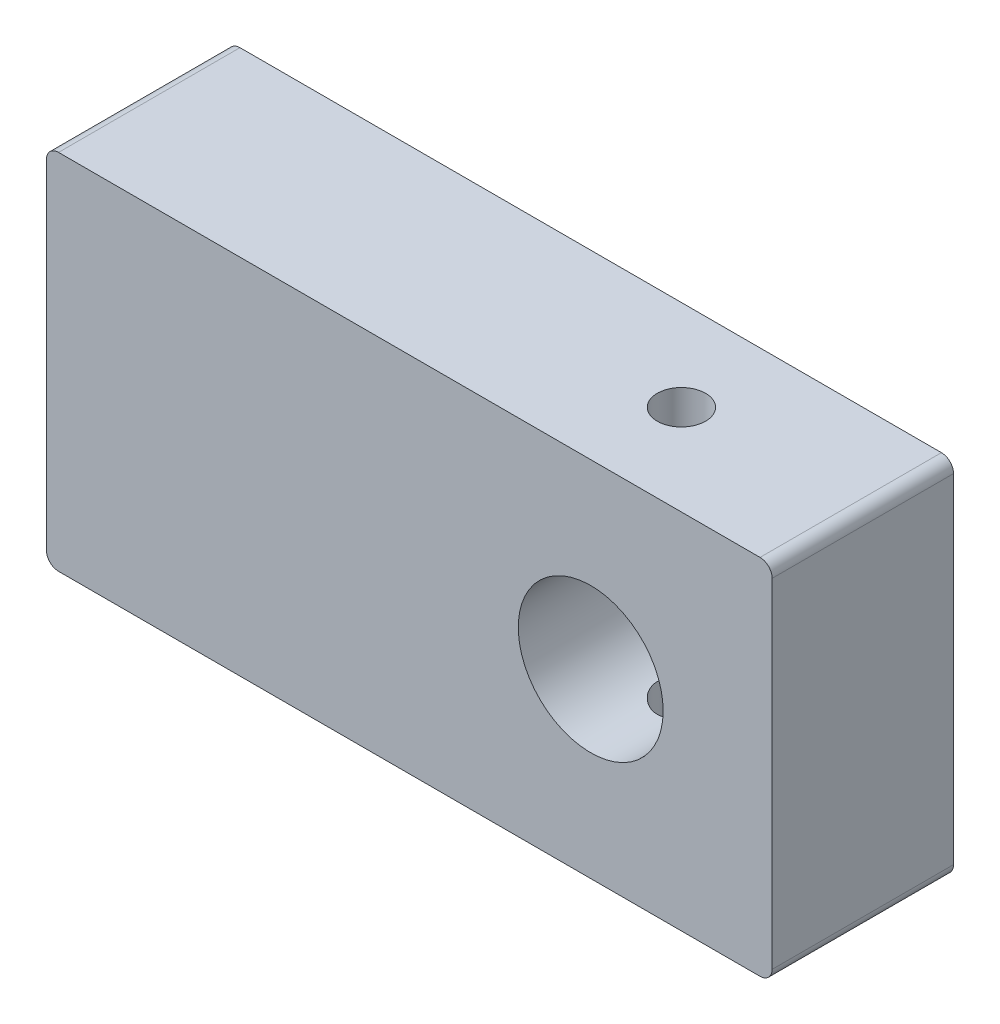
SolidWorks part; units mm, degrees
material "Cedar"
ref_plane "Plan de face" through (0, 0, 0) normal (0, 0, 1) x (1, 0, 0)
ref_plane "Plan de dessus" through (0, 0, 0) normal (0, 1, 0) x (1, 0, 0)
ref_plane "Plan de droite" through (0, 0, 0) normal (1, 0, 0) x (0, 0, -1)
sketch "Sketch1" plane through (0, 0, 0) normal (0, 0, 1) x (1, 0, 0)
  line L1 (-29, 15) -> (29, 15)
  line L2 (-30, 14) -> (-30, -14)
  line L3 (-29, -15) -> (29, -15)
  line L4 (30, 14) -> (30, -14)
  line L5 (-30, 15) -> (30, -15) construction
  line L6 (-30, -15) -> (30, 15) construction
  arc A0 (29, 15) -> (30, 14) centre (29, 14) cw
  arc A1 (29, -15) -> (30, -14) centre (29, -14) ccw
  arc A2 (-30, -14) -> (-29, -15) centre (-29, -14) ccw
  arc A3 (-29, 15) -> (-30, 14) centre (-29, 14) ccw
  circle A4 centre (15, 0) radius 5.99
  point P0 (0, 0)
  dimension "D3" = 1
  dimension "D4" = 11.98
  dimension "D1" = 60
  dimension "D2" = 30
  dimension "D5" = 15
extrude "Boss-Extrude1" add sketch "Sketch1" along normal mid plane 15
sketch "Sketch2" plane through (-30, 0, 0) normal (-1, 0, 0) x (0, 0, 1)
  line L0 (0, -14) -> (0, 14) construction
  line L1 (7.5, -14) -> (-7.5, -14) construction
  line L2 (7.5, 14) -> (-7.5, 14) construction
  circle A0 centre (0, 8) radius 2
  circle A1 centre (0, -8) radius 2
  dimension "D1" = 4
  dimension "D2" = 4
  dimension "D3" = 8
  dimension "D4" = 8
extrude "Cut-Extrude1" cut sketch "Sketch2" against normal blind 15
sketch "Sketch3" plane through (0, 15, 0) normal (0, 1, 0) x (1, 0, 0)
  line L0 (20.99, 0) -> (9.01, 0) construction
  line L3 (20.99, -7.5) -> (20.99, 7.5) construction
  line L4 (9.01, 7.5) -> (9.01, -7.5) construction
  circle A1 centre (15, 0) radius 2
  dimension "D1" = 4
extrude "Cut-Extrude5" cut sketch "Sketch3" against normal blind 35
